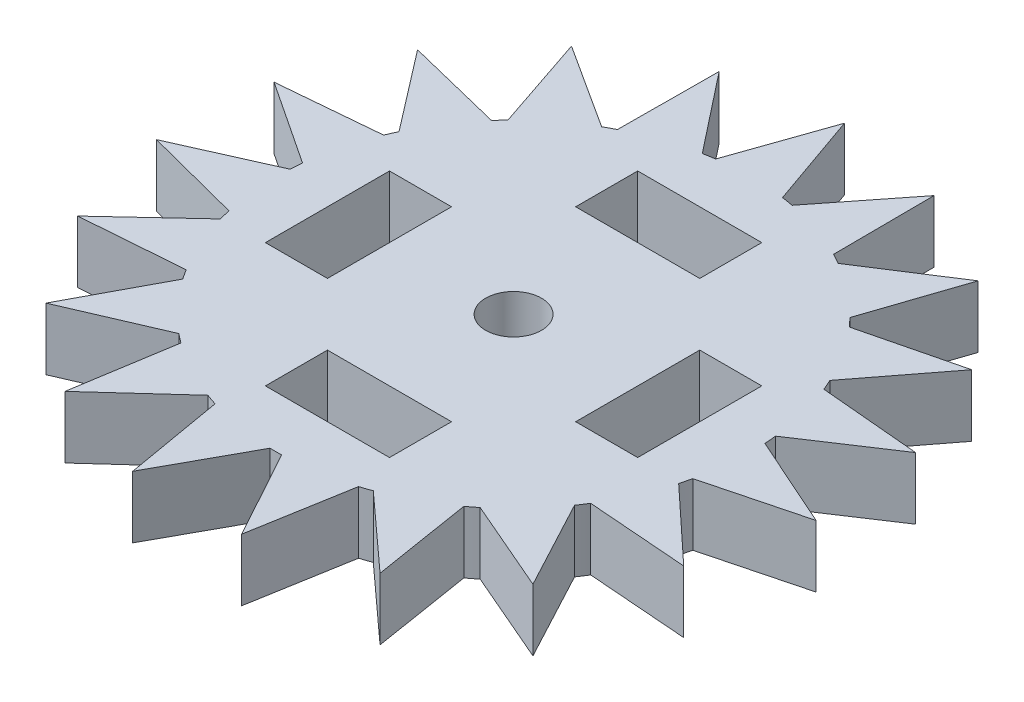
SolidWorks part; units mm, degrees
ref_plane "Front Plane" through (0, 0, 0) normal (0, 0, 1) x (1, 0, 0)
ref_plane "Top Plane" through (0, 0, 0) normal (0, 1, 0) x (1, 0, 0)
ref_plane "Right Plane" through (0, 0, 0) normal (1, 0, 0) x (0, 0, -1)
sketch "Sketch5" plane through (0, 0, 0) normal (0, 1, 0) x (1, 0, 0)
  circle A0 centre (0, 0) radius 11.5
  dimension "D1" = 23
extrude "Boss-Extrude2" add sketch "Sketch5" along normal blind 3
sketch "Sketch1" plane through (0, 0, 0) normal (0, 1, 0) x (1, 0, 0)
  line L0 (0, 0) -> (0, 16) construction
  line L2 (0, 16) -> (-1.75, 11)
  line L3 (-1.75, 11) -> (1.75, 11)
  line L5 (0, 16) -> (1.75, 11)
  line L6 (5.1952, 15.1331) -> (1.9165, 10.9722)
  line L7 (1.9165, 10.9722) -> (5.2269, 9.8358)
  line L8 (5.1952, 15.1331) -> (5.2269, 9.8358)
  line L9 (9.8274, 12.6262) -> (5.3753, 9.7554)
  line L10 (5.3753, 9.7554) -> (8.1373, 7.6057)
  line L11 (9.8274, 12.6262) -> (8.1373, 7.6057)
  line L12 (13.3947, 8.7512) -> (8.2517, 7.4815)
  line L13 (8.2517, 7.4815) -> (10.166, 4.5514)
  line L14 (13.3947, 8.7512) -> (10.166, 4.5514)
  line L15 (15.5104, 3.9278) -> (10.2338, 4.3968)
  line L16 (10.2338, 4.3968) -> (11.093, 1.0039)
  line L17 (15.5104, 3.9278) -> (11.093, 1.0039)
  line L18 (15.9454, -1.3213) -> (11.1069, 0.8357)
  line L19 (11.1069, 0.8357) -> (10.8179, -2.6524)
  line L20 (15.9454, -1.3213) -> (10.8179, -2.6524)
  line L21 (14.6524, -6.4271) -> (10.7765, -2.816)
  line L22 (10.7765, -2.816) -> (9.3705, -6.0213)
  line L23 (14.6524, -6.4271) -> (9.3705, -6.0213)
  line L24 (11.7716, -10.8365) -> (9.2782, -6.1626)
  line L25 (9.2782, -6.1626) -> (6.9077, -8.7376)
  line L26 (11.7716, -10.8365) -> (6.9077, -8.7376)
  line L27 (7.6152, -14.0716) -> (6.7745, -8.8413)
  line L28 (6.7745, -8.8413) -> (3.6963, -10.5071)
  line L29 (7.6152, -14.0716) -> (3.6963, -10.5071)
  line L30 (2.6335, -15.7818) -> (3.5367, -10.5619)
  line L31 (3.5367, -10.5619) -> (0.0844, -11.138)
  line L32 (2.6335, -15.7818) -> (0.0844, -11.138)
  line L33 (-2.6335, -15.7818) -> (-0.0844, -11.138)
  line L34 (-0.0844, -11.138) -> (-3.5367, -10.5619)
  line L35 (-2.6335, -15.7818) -> (-3.5367, -10.5619)
  line L36 (-7.6152, -14.0716) -> (-3.6963, -10.5071)
  line L37 (-3.6963, -10.5071) -> (-6.7745, -8.8413)
  line L38 (-7.6152, -14.0716) -> (-6.7745, -8.8413)
  line L39 (-11.7716, -10.8365) -> (-6.9077, -8.7376)
  line L40 (-6.9077, -8.7376) -> (-9.2782, -6.1626)
  line L41 (-11.7716, -10.8365) -> (-9.2782, -6.1626)
  line L42 (-14.6524, -6.4271) -> (-9.3705, -6.0213)
  line L43 (-9.3705, -6.0213) -> (-10.7765, -2.816)
  line L44 (-14.6524, -6.4271) -> (-10.7765, -2.816)
  line L46 (-15.9454, -1.3213) -> (-10.8179, -2.6524)
  line L47 (-10.8179, -2.6524) -> (-11.1069, 0.8357)
  line L48 (-15.9454, -1.3213) -> (-11.1069, 0.8357)
  line L49 (-15.5104, 3.9278) -> (-11.093, 1.0039)
  line L50 (-11.093, 1.0039) -> (-10.2338, 4.3968)
  line L51 (-15.5104, 3.9278) -> (-10.2338, 4.3968)
  line L52 (-13.3947, 8.7512) -> (-10.166, 4.5514)
  line L53 (-10.166, 4.5514) -> (-8.2517, 7.4815)
  line L54 (-13.3947, 8.7512) -> (-8.2517, 7.4815)
  line L56 (-9.8274, 12.6262) -> (-8.1373, 7.6057)
  line L57 (-8.1373, 7.6057) -> (-5.3753, 9.7554)
  line L58 (-9.8274, 12.6262) -> (-5.3753, 9.7554)
  line L59 (-5.1952, 15.1331) -> (-5.2269, 9.8358)
  line L60 (-5.2269, 9.8358) -> (-1.9165, 10.9722)
  line L61 (-5.1952, 15.1331) -> (-1.9165, 10.9722)
  point P5 (0, 11)
  point P10 (3.5717, 10.404)
  point P14 (6.7563, 8.6805)
  point P18 (9.2088, 6.0164)
  point P22 (10.6634, 2.7003)
  point P26 (10.9624, -0.9084)
  point P30 (10.0735, -4.4186)
  point P34 (8.093, -7.4501)
  point P38 (5.2354, -9.6742)
  point P42 (1.8105, -10.85)
  point P46 (-1.8105, -10.85)
  point P50 (-5.2354, -9.6742)
  point P54 (-8.093, -7.4501)
  point P58 (-10.0735, -4.4186)
  point P64 (-10.9624, -0.9084)
  point P68 (-10.6634, 2.7003)
  point P72 (-9.2088, 6.0164)
  point P74 (-6.7563, 8.6805)
  point P78 (-3.5717, 10.404)
  dimension "D2" = 16
  dimension "D1" = 5
  dimension "D3" = 3.5
  dimension "D4" = 19
extrude "Boss-Extrude1" add sketch "Sketch1" along normal blind 3
sketch "Sketch3" plane through (0, 0, 0) normal (0, 1, 0) x (1, 0, 0)
  line L0 (0, 0) -> (0, 9) construction
  line L1 (3, 9) -> (-3, 9)
  line L2 (-3, 9) -> (-3, 6)
  line L3 (-3, 6) -> (3, 6)
  line L4 (3, 9) -> (3, 6)
  line L5 (0.75, 4.5) -> (-0.75, 4.5) construction
  line L6 (-0.75, 4.5) -> (-0.75, 3) construction
  line L7 (-0.75, 3) -> (0.75, 3) construction
  line L8 (0.75, 4.5) -> (0.75, 3) construction
  line L9 (9, -3) -> (6, -3)
  line L10 (6, 3) -> (6, -3)
  line L11 (9, 3) -> (6, 3)
  line L12 (9, -3) -> (9, 3)
  line L17 (-3, -9) -> (-3, -6)
  line L18 (3, -6) -> (-3, -6)
  line L19 (3, -9) -> (3, -6)
  line L20 (-3, -9) -> (3, -9)
  line L21 (-0.75, -4.5) -> (-0.75, -3) construction
  line L22 (0.75, -3) -> (-0.75, -3) construction
  line L23 (0.75, -4.5) -> (0.75, -3) construction
  line L24 (-0.75, -4.5) -> (0.75, -4.5) construction
  line L25 (-9, 3) -> (-6, 3)
  line L26 (-6, -3) -> (-6, 3)
  line L27 (-9, -3) -> (-6, -3)
  line L28 (-9, 3) -> (-9, -3)
  line L33 (-4.5, 0.75) -> (-3, 0.75) [skipped]
  line L34 (-3, -0.75) -> (-3, 0.75) [skipped]
  line L35 (-4.5, -0.75) -> (-3, -0.75) [skipped]
  line L36 (-4.5, 0.75) -> (-4.5, -0.75) [skipped]
  line L37 (4.5, -0.75) -> (3, -0.75) [skipped]
  line L38 (3, 0.75) -> (3, -0.75) [skipped]
  line L39 (4.5, 0.75) -> (3, 0.75) [skipped]
  line L40 (4.5, -0.75) -> (4.5, 0.75) [skipped]
  point P6 (0, 3)
  point P8 (0, 6)
  point P14 (0, 4.5)
  dimension "D1" = 9
  dimension "D2" = 6
  dimension "D3" = 3
  dimension "D4" = 1.5
  dimension "D5" = 1.5
  dimension "D6" = 4
extrude "Cut-Extrude1" cut sketch "Sketch3" along normal up to surface (3 mm away) up to face at (0, 3, 0)
sketch "Sketch6" plane through (0, 3, 0) normal (0, 1, 0) x (1, 0, 0)
  circle A0 centre (0, 0) radius 1.35
  dimension "D1" = 2.7
extrude "Cut-Extrude3" cut sketch "Sketch6" against normal up to surface (3 mm away) up to face at (7.5, 0, 0)
sketch "Sketch7" plane through (0, 3, 0) normal (0, 1, 0) x (1, 0, 0)
  circle A0 centre (0, 4) radius 1.35
  dimension "D2" = 2.7
  dimension "D1" = 4
extrude "Cut-Extrude4" [suppressed] cut sketch "Sketch7" against normal up to surface (3 mm away)
equation "\"t\"=2.5"
equation "\"h\"= 2.5"
